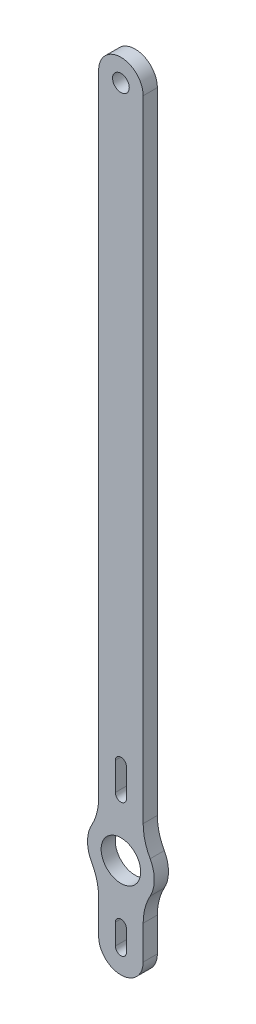
SolidWorks part; units mm, degrees
ref_plane "Front Plane" through (0, 0, 0) normal (0, 0, 1) x (1, 0, 0)
ref_plane "Top Plane" through (0, 0, 0) normal (0, 1, 0) x (1, 0, 0)
ref_plane "Right Plane" through (0, 0, 0) normal (1, 0, 0) x (0, 0, -1)
sketch "Model" plane through (0, 0, 0) normal (0, 0, 1) x (1, 0, 0)
  line L0 (-1, 18.4215) -> (-1, -3.4062) construction
  line L1 (1, 18.4215) -> (1, 5.9161) construction
  line L7 (-7.5978, 10.1) -> (4.5933, 10.1) construction
  line L8 (-1.9126, -10.1) -> (1, -10.1) construction
  line L9 (-3.5953, 15.1) -> (3.0222, 15.1) construction
  line L10 (-2.3019, -13.8) -> (3.0222, -13.8) construction
  line L11 (-4, 121) -> (-4, 7.746)
  line L12 (4, 121) -> (4, 7.746)
  line L13 (-1, -10.1) -> (-1, -13.8)
  line L14 (1, -10.1) -> (1, -13.8)
  line L15 (-1, 15.1) -> (-1, 10.1)
  line L16 (1, 15.1) -> (1, 10.1)
  line L17 (1, 3.4062) -> (1, -5.9161) construction
  line L18 (1, -10.1) -> (1, -18.7667) construction
  line L19 (-1, -5.9161) -> (-1, -18.7667) construction
  line L20 (-4, -7.746) -> (-4, -13.8)
  line L21 (4, -7.746) -> (4, -13.8)
  circle A0 centre (0, 0) radius 3.55
  arc A1 (-5.25, 2.9047) -> (-5.25, -2.9047) centre (0, 0) ccw
  arc A2 (1, 15.1) -> (-1, 15.1) centre (0, 15.1) ccw
  arc A3 (-1, 10.1) -> (1, 10.1) centre (0, 10.1) ccw
  arc A4 (1, -10.1) -> (-1, -10.1) centre (0, -10.1) ccw
  arc A5 (-1, -13.8) -> (1, -13.8) centre (0, -13.8) ccw
  circle A6 centre (0, 121) radius 1.5
  arc A7 (4, 121) -> (-4, 121) centre (0, 121) ccw
  arc A8 (-4, -13.8) -> (4, -13.8) centre (0, -13.8) ccw
  arc A9 (5.25, -2.9047) -> (5.25, 2.9047) centre (0, 0) ccw
  arc A10 (4, 7.746) -> (5.25, 2.9047) centre (14, 7.746) ccw
  arc A11 (5.25, -2.9047) -> (4, -7.746) centre (14, -7.746) ccw
  arc A12 (-5.25, -2.9047) -> (-4, -7.746) centre (-14, -7.746) cw
  arc A13 (-5.25, 2.9047) -> (-4, 7.746) centre (-14, 7.746) ccw
  point P44 (4, -4.4721)
  point P47 (-4, -4.4721)
  dimension "D1" = 7.1
  dimension "D2" = 12
  dimension "D15" = 3
  dimension "D5" = 10
  dimension "D3" = 1
  dimension "D4" = 1
  dimension "D9" = 10.1
  dimension "D10" = 10.1
  dimension "D11" = 3.7
  dimension "D12" = 5
  dimension "D13" = 4
  dimension "D14" = 4
  dimension "D16" = 121
extrude "Boss-Extrude1" add sketch "Model" along normal blind 2.55
